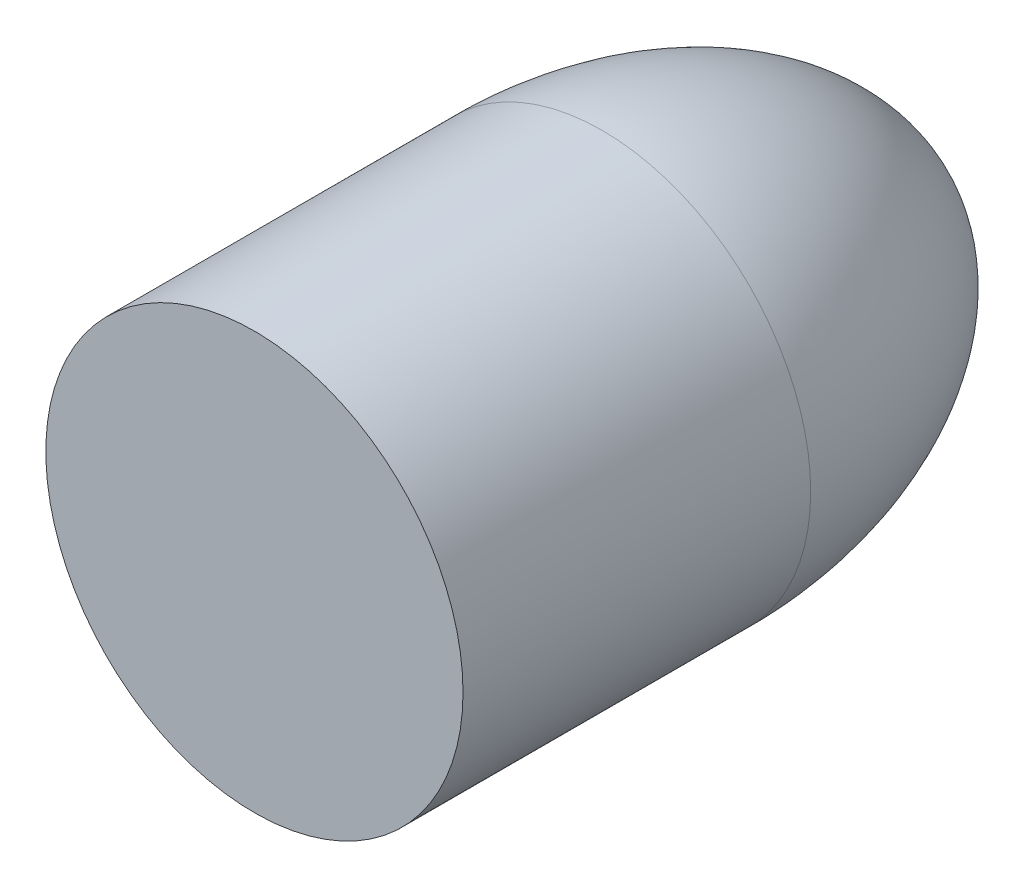
SolidWorks part; units mm, degrees
other "Markup1"
sketch "Sketch3" plane through (-76.2, 76.2, -762) normal (-0.6807, 0.6563, -0.3256) x (-0.115, 0.3432, 0.9322)
ref_plane "Front Plane" through (0, 0, 0) normal (0, 0, 1) x (1, 0, 0)
ref_plane "Top Plane" through (0, 0, 0) normal (0, 1, 0) x (1, 0, 0)
ref_plane "Right Plane"
sketch "Sketch1" plane through (0, 0, 0) normal (1, 0, 0) x (0, 0, -1)
  line L0 (0, 76.2) -> (0, 0)
  line L1 (0, 0) -> (114.3, 0)
  spline S0 degree 4 poles (-11.4301, 75.818) (-10.8874, 75.8544) (-9.8023, 75.9224) (-8.179, 76.0106) (-5.9939, 76.1006) (-4.0469, 76.1572) (-2.2502, 76.1883) (-0.6558, 76.2004) (0.4432, 76.201) (1.6654, 76.1931) (2.8464, 76.178) (4.2734, 76.1497) (5.9638, 76.1007) (7.9606, 76.0214) (10.2286, 75.9006) (12.4995, 75.7494) (14.7662, 75.5678) (17.5973, 75.3028) (20.988, 74.9236) (24.9332, 74.3914) (29.4234, 73.659) (33.8914, 72.8009) (38.333, 71.8154) (43.8468, 70.4219) (50.3926, 68.4866) (57.9042, 65.8341) (66.2689, 62.2371) (74.1902, 58.1309) (80.806, 54.0277) (86.1921, 50.1371) (90.4506, 46.6495) (93.8221, 43.5925) (97.0253, 40.3592) (100.0391, 36.9484) (102.8402, 33.3603) (105.4029, 29.5977) (107.6998, 25.6668) (109.7023, 21.5774) (111.3817, 17.3446) (112.8007, 12.6931) (113.8092, 7.8046) (114.2102, 3.972) (114.3, 1.2633) (114.3, 0) knots 0 0 0 0 0 0.013373 0.026745 0.040118 0.05349 0.061928 0.070366 0.077362 0.084358 0.091354 0.09835 0.112342 0.126334 0.140326 0.154318 0.16831 0.182303 0.210287 0.238271 0.266255 0.294239 0.322223 0.350207 0.406175 0.462143 0.518111 0.574079 0.625518 0.653502 0.681486 0.70947 0.737454 0.765439 0.793422 0.821407 0.84939 0.877373 0.905359 0.933344 0.968916 1 1 1 1 1 construction
  spline S1 degree 4 poles (0, 76.2) (0.2643, 76.2) (0.7937, 76.1987) (1.6654, 76.1931) (2.8464, 76.178) (4.2734, 76.1497) (5.9638, 76.1007) (7.9606, 76.0214) (10.2286, 75.9006) (12.4995, 75.7494) (14.7662, 75.5678) (17.5973, 75.3028) (20.988, 74.9236) (24.9332, 74.3914) (29.4234, 73.659) (33.8914, 72.8009) (38.333, 71.8154) (43.8468, 70.4219) (50.3926, 68.4866) (57.9042, 65.8341) (66.2689, 62.2371) (74.1902, 58.1309) (80.806, 54.0277) (86.1921, 50.1371) (90.4506, 46.6495) (93.8221, 43.5925) (97.0253, 40.3592) (100.0391, 36.9484) (102.8402, 33.3603) (105.4029, 29.5977) (107.6998, 25.6668) (109.7023, 21.5774) (111.3817, 17.3446) (112.8007, 12.6931) (113.8092, 7.8046) (114.2102, 3.972) (114.3, 1.2633) (114.3, 0) knots 0.070366 0.070366 0.070366 0.070366 0.070366 0.077362 0.084358 0.091354 0.09835 0.112342 0.126334 0.140326 0.154318 0.16831 0.182303 0.210287 0.238271 0.266255 0.294239 0.322223 0.350207 0.406175 0.462143 0.518111 0.574079 0.625518 0.653502 0.681486 0.70947 0.737454 0.765439 0.793422 0.821407 0.84939 0.877373 0.905359 0.933344 0.968916 1 1 1 1 1
ref_axis "Axis1" through (0, 0, -480.06) along (0, 0, 1)
revolve "Revolve1" add sketch "Sketch1" angle 360 about axis through (0, 0, -480.06) along (0, 0, 1)
sketch "Sketch2" plane through (0, 0, 0) normal (0, 0, 1) x (1, 0, 0)
  circle A0 centre (0, 0) radius 76.2
  dimension "D1" = 152.4
extrude "Boss-Extrude1" add sketch "Sketch2" along normal blind 127
equation "\"BodyTubeRadius\"= 3in"
equation "\"ratio\"= 0.75"
equation "\"NoseConeLength\"= \"ratio\" * 2 * \"BodyTubeRadius\""
equation "\"D1@Sketch2\"=2*\"BodyTubeRadius\""
equation "\"BodyTubeLength\"=5"
